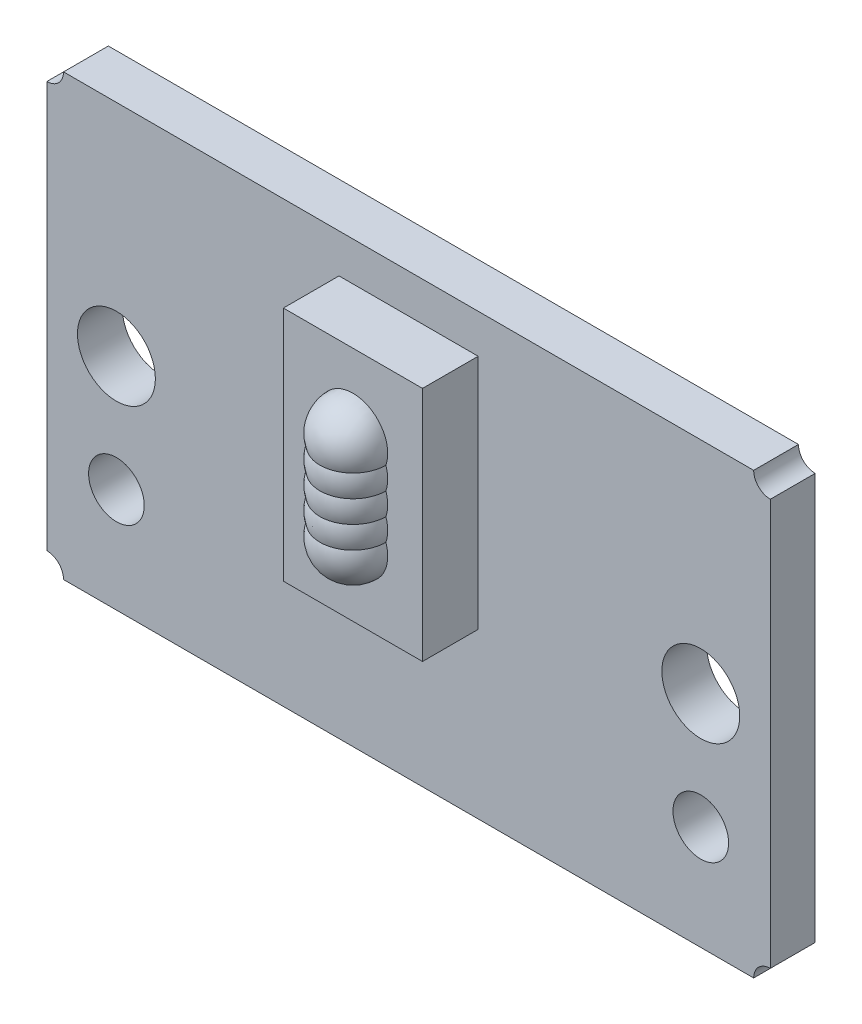
SolidWorks part; units mm, degrees
ref_plane "Front Plane" through (0, 0, 0) normal (0, 0, 1) x (1, 0, 0)
ref_plane "Top Plane" through (0, 0, 0) normal (0, 1, 0) x (1, 0, 0)
ref_plane "Right Plane" through (0, 0, 0) normal (1, 0, 0) x (0, 0, -1)
sketch "Sketch1" plane through (0, 0, 0) normal (0, 0, 1) x (1, 0, 0)
  line L1 (-13, 7.9) -> (13, 7.9)
  line L2 (-13, 7.9) -> (-13, -7.9)
  line L3 (-13, -7.9) -> (13, -7.9)
  line L4 (13, 7.9) -> (13, -7.9)
  line L5 (-13, 7.9) -> (13, -7.9) construction
  line L6 (-13, -7.9) -> (13, 7.9) construction
  point P0 (0, 0)
  dimension "D1" = 26
  dimension "D2" = 15.8
extrude "Boss-Extrude1" add sketch "Sketch1" along normal blind 1.61
sketch "Sketch2" plane through (0, 0, 1.61) normal (0, 0, 1) x (1, 0, 0)
  circle A0 centre (-13, 7.9) radius 0.6
  circle A1 centre (-13, -7.9) radius 0.6
  circle A2 centre (13, -7.9) radius 0.6
  circle A3 centre (13, 7.9) radius 0.6
  dimension "D1" = 1.2
extrude "Cut-Extrude1" cut sketch "Sketch2" against normal blind 1.61
sketch "Sketch3" plane through (0, 0, 1.61) normal (0, 0, 1) x (1, 0, 0)
  circle A0 centre (-10.5, 0) radius 1.4
  circle A1 centre (10.5, 0) radius 1.4
  circle A2 centre (-10.5, -4.15) radius 1
  circle A3 centre (10.5, -4.15) radius 1
  dimension "D1" = 2.8
  dimension "D2" = 10.5
  dimension "D4" = 2
  dimension "D5" = 4.15
  dimension "D3" = 10.5
extrude "Cut-Extrude2" cut sketch "Sketch3" against normal blind 11.61
sketch "Sketch4" plane through (0, 0, 1.61) normal (0, 0, 1) x (1, 0, 0)
  line L6 (-2.5, 6.5) -> (2.5, 6.5)
  line L7 (-2.5, 6.5) -> (-2.5, -2)
  line L8 (-2.5, -2) -> (2.5, -2)
  line L9 (2.5, 6.5) -> (2.5, -2)
  line L10 (-2.5, 6.5) -> (2.5, -2) construction
  line L11 (-2.5, -2) -> (2.5, 6.5) construction
  line L12 (12.4, 7.9) -> (-12.4, 7.9) construction
  point P0 (0, 2.25)
  dimension "D1" = 8.5
  dimension "D2" = 5
  dimension "D3" = 9.9
extrude "Boss-Extrude2" add sketch "Sketch4" along normal blind 2
sketch "Sketch5" plane through (0, 0, 3.61) normal (0, 0, 1) x (1, 0, 0)
  line L0 (-2.5, 6.5) -> (2.5, -2) construction
  line L1 (1.25, 2.25) -> (-1.25, 2.25)
  arc A0 (1.25, 2.25) -> (-1.25, 2.25) centre (0, 2.25) ccw
  point P7 (0, 2.25)
  point P8 (0, 0)
  dimension "D1" = 1.25
revolve "Revolve1" add sketch "Sketch5" angle 360 about L1
pattern_linear "LPattern1" count 3 spacing 0.8 along (0, -1, 0) count 3 spacing 0.8 along (0, 1, 0) of "Revolve1"
sketch "Sketch6" plane through (0, 0, 3.61) normal (0, 0, 1) x (1, 0, 0)
  line L4 (2.5, -2) -> (2.5, 6.5)
  line L5 (2.5, 6.5) -> (-2.5, 6.5)
  line L6 (-2.5, 6.5) -> (-2.5, -2)
  line L7 (-2.5, -2) -> (2.5, -2)
  line L8 (2.5, -2) -> (2.5, 6.5)
  line L9 (2.5, 6.5) -> (-2.5, 6.5)
  line L10 (-2.5, 6.5) -> (-2.5, -2)
  line L11 (-2.5, -2) -> (2.5, -2)
  dimension "D1" = 0
